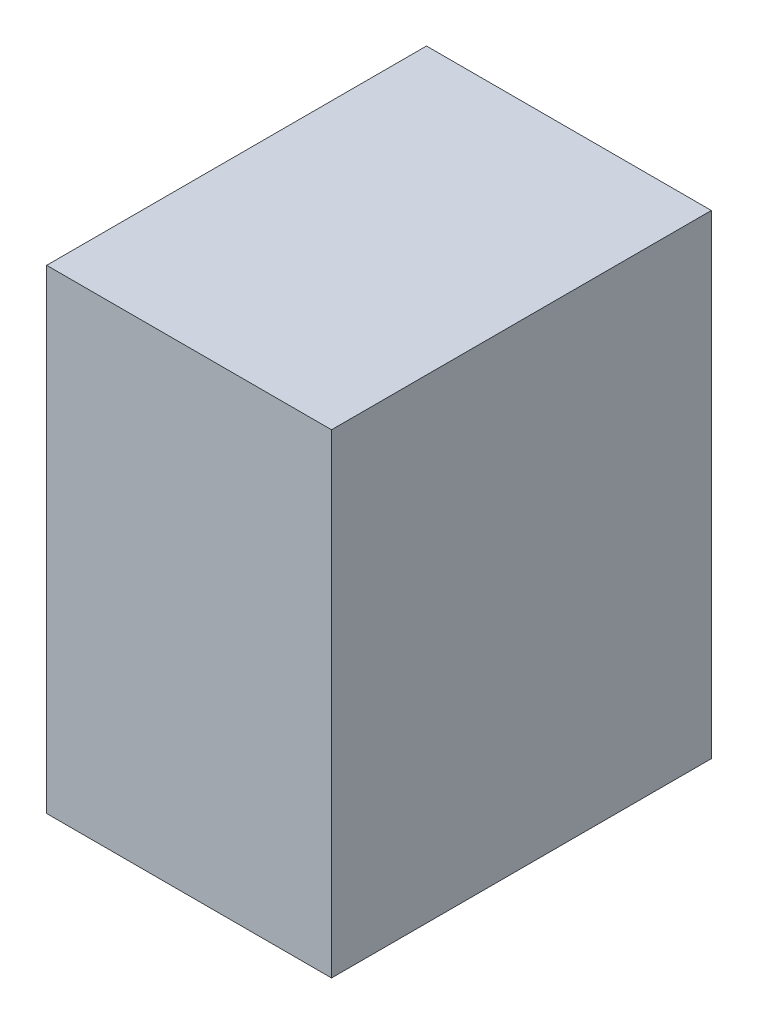
SolidWorks part; units mm, degrees
ref_plane "前视基准面" through (0, 0, 0) normal (0, 0, 1) x (1, 0, 0)
ref_plane "上视基准面" through (0, 0, 0) normal (0, 1, 0) x (1, 0, 0)
ref_plane "右视基准面" through (0, 0, 0) normal (1, 0, 0) x (0, 0, -1)
other "Configuration Table"
sketch "草图1" plane through (0, 0, 0) normal (0, 1, 0) x (1, 0, 0)
  line L0 (-60.6592, -10.3261) -> (-57.6592, -10.3261)
  line L1 (-60.6592, -10.3261) -> (-60.6592, -6.3261)
  line L2 (-57.6592, -10.3261) -> (-57.6592, -6.3261)
  line L3 (-60.6592, -6.3261) -> (-57.6592, -6.3261)
extrude "凸台-拉伸1" add sketch "草图1" along normal blind 5
sketch "草图2" plane through (0, 0, 0) normal (0, -1, 0) x (1, 0, 0)
  line L0 (-59.1592, 10.3261) -> (-59.1592, 6.3261)
  line L1 (-60.6592, 10.3261) -> (-57.6592, 10.3261) construction
  line L2 (-57.6592, 6.3261) -> (-60.6592, 6.3261) construction
  line L3 (-60.6592, 8.3261) -> (-57.6592, 8.3261)
  line L4 (-60.6592, 6.3261) -> (-60.6592, 10.3261) construction
  line L5 (-57.6592, 10.3261) -> (-57.6592, 6.3261) construction
  line L7 (-60.1592, 6.5761) -> (-58.1592, 6.5761)
  line L8 (-60.1592, 6.5761) -> (-60.1592, 10.0761)
  line L9 (-60.1592, 10.0761) -> (-58.1592, 10.0761)
  line L10 (-58.1592, 6.5761) -> (-58.1592, 10.0761)
  line L11 (-60.1592, 6.5761) -> (-58.1592, 10.0761) construction
  line L12 (-60.1592, 10.0761) -> (-58.1592, 6.5761) construction
  point P12 (-59.1592, 8.3261)
extrude "切除-拉伸1" cut sketch "草图2" against normal blind 4 contours L3 L10 L9 L0 | L7 L10 L3 L0 | L8 L7 L0 L3 | L9 L8 L3 L0
